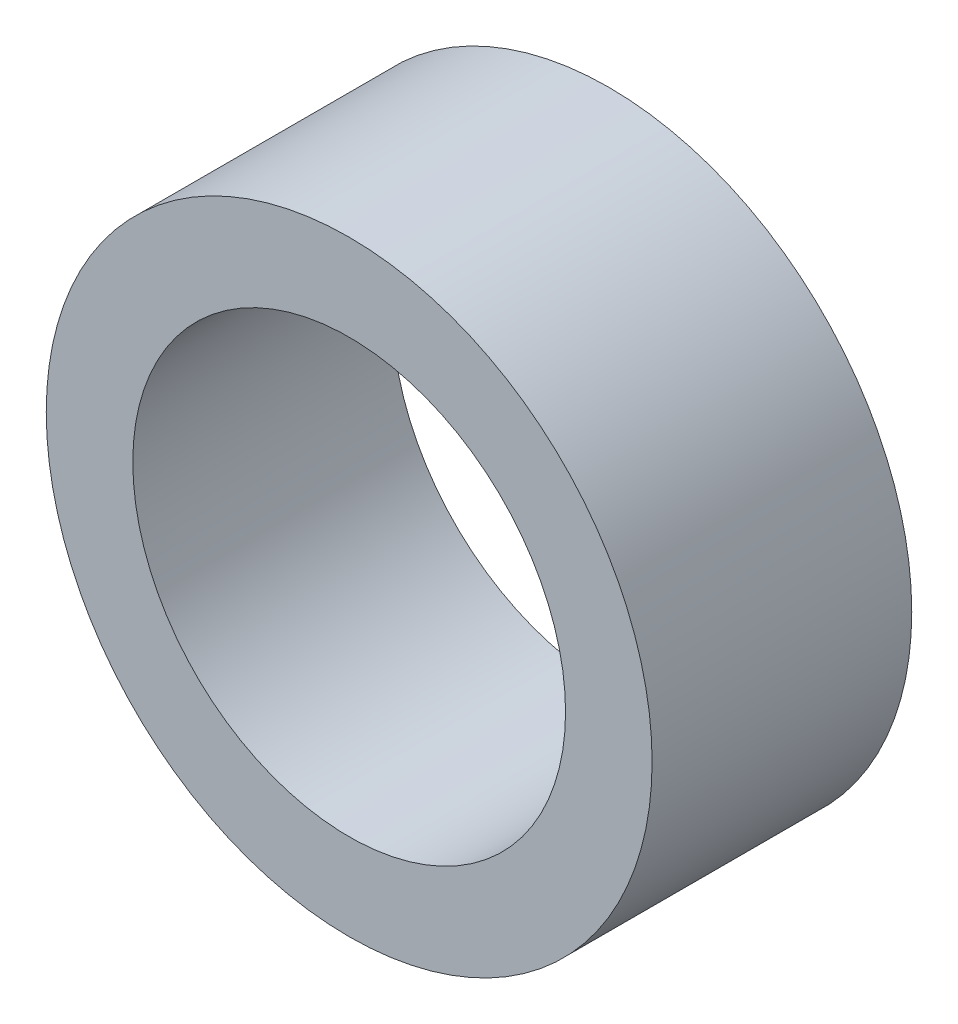
SolidWorks part; units mm, degrees
ref_plane "Front Plane" through (0, 0, 0) normal (0, 0, 1) x (1, 0, 0)
ref_plane "Top Plane" through (0, 0, 0) normal (0, 1, 0) x (1, 0, 0)
ref_plane "Right Plane" through (0, 0, 0) normal (1, 0, 0) x (0, 0, -1)
sketch "Sketch1" plane through (0, 0, 0) normal (0, 0, 1) x (1, 0, 0)
  circle A0 centre (0, 0) radius 31.75
  circle A1 centre (0, 0) radius 44.45
  dimension "D1" = 63.5
  dimension "D2" = 88.9
extrude "Boss-Extrude1" add sketch "Sketch1" against normal blind 38.1 from offset 19.05
